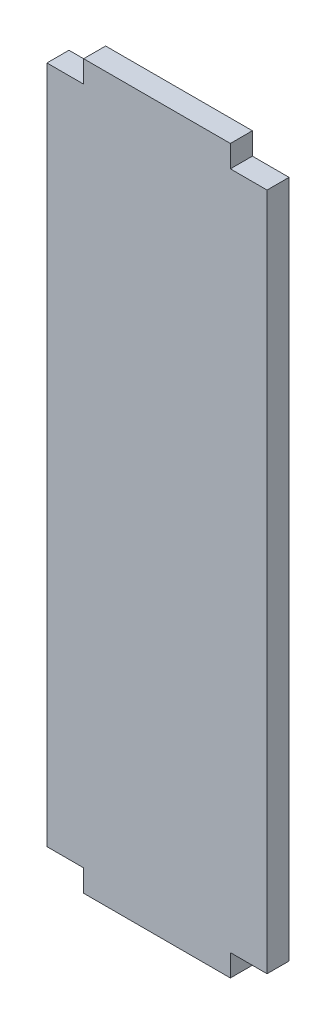
SolidWorks part; units mm, degrees
material "Pine"
ref_plane "Front Plane" through (0, 0, 0) normal (0, 0, 1) x (1, 0, 0)
ref_plane "Top Plane" through (0, 0, 0) normal (0, 1, 0) x (1, 0, 0)
ref_plane "Right Plane" through (0, 0, 0) normal (1, 0, 0) x (0, 0, -1)
sketch "Sketch1" plane through (0, 0, 0) normal (0, 0, 1) x (1, 0, 0)
  line L0 (-30, 92.5) -> (-30, -92.5)
  line L1 (-30, -92.5) -> (-20, -92.5)
  line L2 (-20, -92.5) -> (-20, -98.5)
  line L3 (-20, -98.5) -> (20, -98.5)
  line L4 (20, -98.5) -> (20, -92.5)
  line L5 (20, -92.5) -> (30, -92.5)
  line L6 (30, -92.5) -> (30, 92.5)
  line L7 (30, 92.5) -> (20, 92.5)
  line L8 (20, 92.5) -> (20, 98.5)
  line L9 (20, 98.5) -> (-20, 98.5)
  line L10 (-20, 98.5) -> (-20, 92.5)
  line L11 (-20, 92.5) -> (-30, 92.5)
  point P2 (0, 0)
  point P13 (0, 0)
  point P14 (-30, 0)
  point P16 (0, 98.5)
  point P17 (-18.9181, 53.5755)
  point P18 (0, 0)
  point P19 (0, 0)
  dimension "D1" = 40
  dimension "D2" = 60
  dimension "D3" = 6
  dimension "D4" = 185
extrude "Boss-Extrude1" add sketch "Sketch1" along normal blind 6
